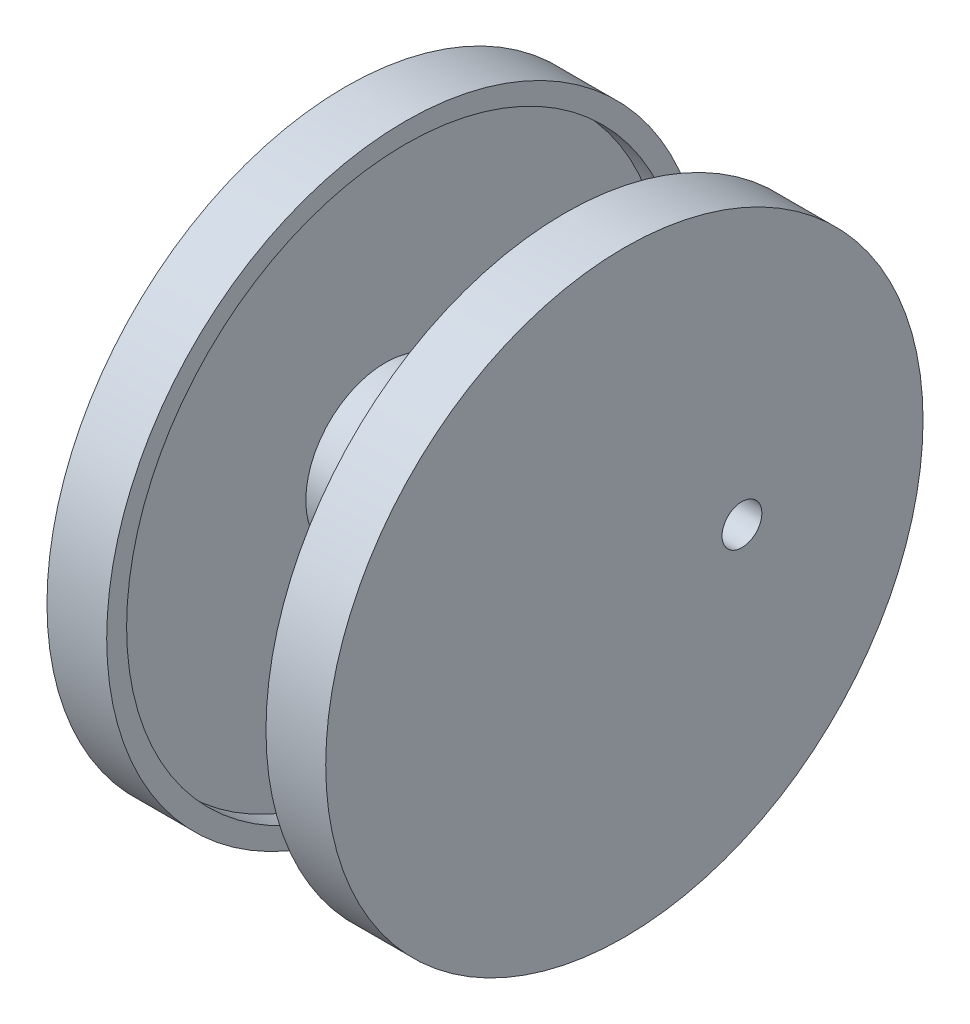
SolidWorks part; units mm, degrees
ref_plane "Front" through (0, 0, 0) normal (0, 0, 1) x (1, 0, 0)
ref_plane "Top" through (0, 0, 0) normal (0, 1, 0) x (1, 0, 0)
ref_plane "Right" through (0, 0, 0) normal (1, 0, 0) x (0, 0, -1)
sketch "Sketch1" plane through (0, 0, 0) normal (0, 0, 1) x (1, 0, 0)
  line L0 (-52.1154, 0) -> (17.8846, 0)
  line L1 (-52.1154, 0) -> (-52.1154, 75)
  line L2 (-52.1154, 75) -> (-37.1154, 75)
  line L3 (-37.1154, 75) -> (-37.1154, 70)
  line L4 (-37.1154, 70) -> (-42.1154, 70)
  line L5 (-42.1154, 70) -> (-42.1154, 20)
  line L6 (-42.1154, 20) -> (7.8846, 20)
  line L7 (7.8846, 20) -> (7.8846, 70)
  line L8 (7.8846, 70) -> (2.8846, 70)
  line L9 (2.8846, 70) -> (2.8846, 75)
  line L10 (2.8846, 75) -> (17.8846, 75)
  line L11 (17.8846, 75) -> (17.8846, 0)
  line L12 (-114.1966, 0) -> (101.9563, 0) construction
  dimension "D1" = 70
  dimension "D2" = 75
  dimension "D3" = 10
  dimension "D4" = 5
  dimension "D5" = 50
  dimension "D6" = 20
  dimension "D7" = 15
  dimension "D8" = 5
  dimension "D9" = 75
  dimension "D10" = 70
revolve "Revolve2" add sketch "Sketch1" angle 360 about L12
sketch "Sketch2" plane through (-52.1154, 0, 0) normal (-1, 0, 0) x (0, 0, 1)
  line L0 (-18.8896, 71.5485) -> (-17.5148, 65.7057)
  line L1 (18.8896, 71.5485) -> (17.5148, 65.7057)
  arc A2 (18.8896, 71.5485) -> (-18.8896, 71.5485) centre (0, 0) ccw
  arc A3 (17.5148, 65.7057) -> (-17.5148, 65.7057) centre (0, 0) ccw
  dimension "D1" = 68
extrude "Cut-Extrude1" cut sketch "Sketch2" against normal blind 5
pattern_circular "CirPattern1" count 5 over 360 about axis through (0, 0, 0) along (1, 0, 0) of "Cut-Extrude1"
sketch "Sketch4" plane through (17.8846, 0, 0) normal (1, 0, 0) x (0, 0, -1)
  circle A0 centre (29.5197, 0) radius 5
extrude "Cut-Extrude4" cut sketch "Sketch4" against normal blind 16 contours A0
